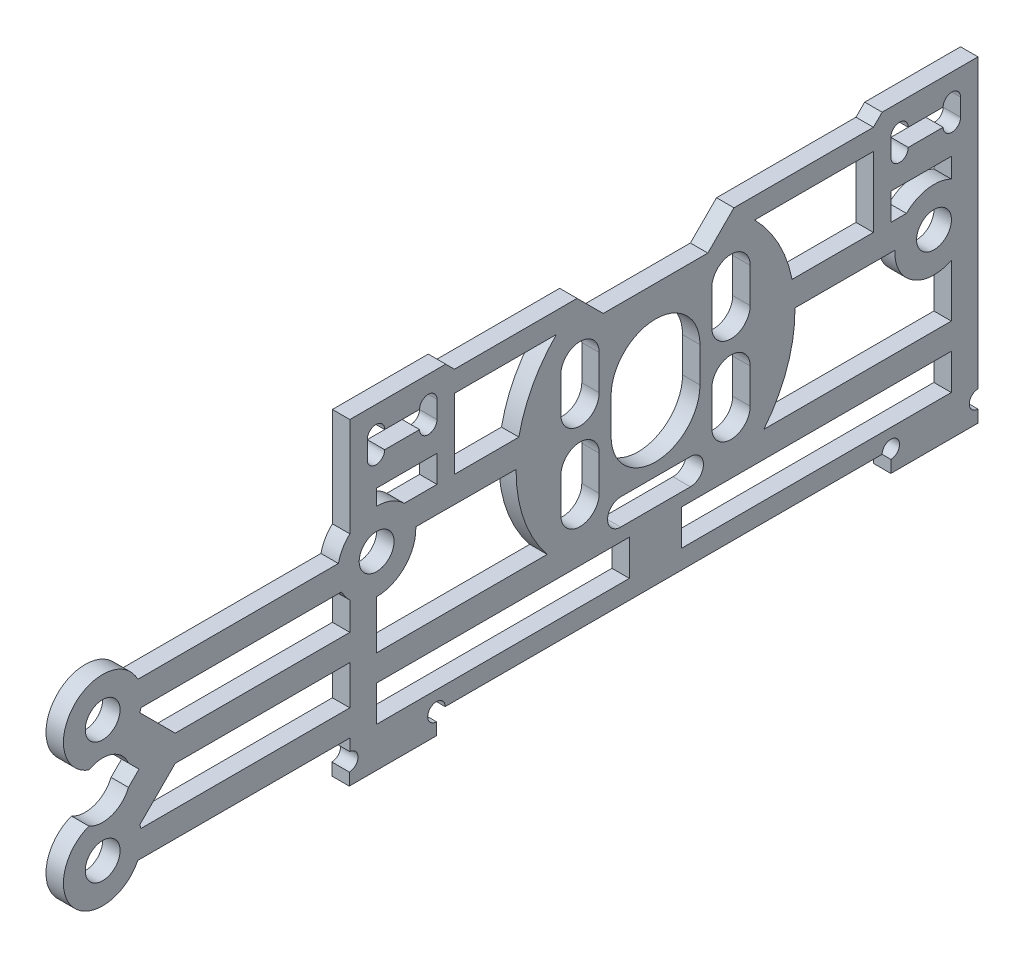
SolidWorks part; units mm, degrees
ref_plane "前视基准面" through (0, 0, 0) normal (0, 0, 1) x (1, 0, 0)
ref_plane "上视基准面" through (0, 0, 0) normal (0, 1, 0) x (1, 0, 0)
ref_plane "右视基准面" through (0, 0, 0) normal (1, 0, 0) x (0, 0, -1)
other "Configuration Table"
sketch "草图1" plane through (0, 0, 0) normal (1, 0, 0) x (0, 0, -1)
  line L11 (-27.6308, 1) -> (-27.6308, -1.7) construction
  line L41 (-27.6308, -1.7) -> (49.3482, -1.7) construction
  line L42 (21.9394, 13) -> (21.9394, 18) construction
  line L48 (21.9394, 11.675) -> (21.9394, 13.675) construction
  line L54 (26.2694, 16.1749) -> (26.2694, 14.1749) construction
  line L64 (19.3894, 11.675) -> (19.3894, 13.675)
  line L77 (24.4894, 11.675) -> (24.4894, 13.675)
  line L85 (17.6103, 9.1756) -> (17.6103, 11.1756) construction
  line L88 (27.3694, 16.1749) -> (27.3694, 14.1749)
  line L107 (25.1694, 16.1749) -> (25.1694, 14.1749)
  line L113 (16.5103, 9.1756) -> (16.5103, 11.1756)
  line L133 (18.7103, 9.1756) -> (18.7103, 11.1756)
  line L139 (26.2685, 9.1756) -> (26.2685, 11.1756) construction
  line L150 (27.3685, 9.1756) -> (27.3685, 11.1756)
  line L151 (25.1685, 9.1756) -> (25.1685, 11.1756)
  line L152 (17.6094, 16.1749) -> (17.6094, 14.1749) construction
  line L153 (16.5094, 16.1749) -> (16.5094, 14.1749)
  line L154 (18.7094, 16.1749) -> (18.7094, 14.1749)
  line L215 (40.5394, 11.675) -> (5.9394, 11.675) construction
  line L229 (35.4394, 1.8) -> (35.4394, 2.5)
  line L254 (40.4394, 2.5) -> (40.4394, 1.8)
  line L255 (9.8715, 3) -> (34.9394, 3)
  line L256 (4.3715, 2.5) -> (4.3715, 1.8)
  line L257 (4.8719, 3) -> (3.8711, 3) construction
  line L259 (-8.2953, 9.2793) -> (-7.691, 8.675)
  line L260 (9.3715, 1.8) -> (9.3715, 2.5)
  line L261 (9.8715, 3) -> (8.8715, 3) construction
  line L269 (10.403, 17.8) -> (10.403, 14.275)
  line L273 (4.403, 17.8) -> (4.403, 14.3188)
  line L282 (40.4394, 14.275) -> (40.4394, 3.5)
  line L284 (40.4394, 17.8) -> (40.4394, 14.275)
  line L287 (34.4394, 17.8) -> (34.4394, 14.275)
  line L302 (4.403, 4.175) -> (4.403, 3.499)
  line L304 (4.403, 17.8) -> (4.403, 18.3)
  line L305 (36.4394, 17.5) -> (38.4394, 17.5)
  line L307 (-7.7613, 13.175) -> (3.7457, 13.175)
  line L308 (4.3715, 1.8) -> (9.3715, 1.8)
  line L311 (34.4394, 17.8) -> (34.4394, 18.3)
  line L312 (4.403, 18.3) -> (4.403, 19.5)
  line L313 (40.4394, 18.3) -> (40.4394, 17.8)
  line L314 (6.403, 18.5) -> (8.403, 18.5)
  line L317 (10.403, 18.3) -> (10.403, 17.8)
  line L321 (40.4394, 19.5) -> (40.4394, 18.3)
  line L322 (10.403, 19.5) -> (17.4394, 19.5)
  line L326 (10.403, 14.275) -> (14.101, 14.275)
  line L330 (10.403, 18.3) -> (16.2508, 18.3)
  line L331 (34.4394, 14.275) -> (29.7778, 14.275)
  line L332 (27.628, 18.3) -> (34.4394, 18.3)
  line L333 (5.403, 18.5) -> (5.403, 17.5)
  line L334 (26.4394, 19.5) -> (34.4394, 19.5)
  line L353 (9.403, 18.5) -> (9.403, 17.5)
  line L354 (6.403, 17.5) -> (8.403, 17.5)
  line L355 (35.4394, 18.5) -> (35.4394, 17.5)
  line L356 (36.4394, 18.5) -> (38.4394, 18.5)
  line L357 (39.4394, 18.5) -> (39.4394, 17.5)
  line L358 (4.403, 19.5) -> (4.403, 20)
  line L359 (40.4394, 19.5) -> (40.4394, 20)
  line L360 (40.4394, 20) -> (34.9394, 20)
  line L361 (34.9394, 20) -> (34.4394, 19.5)
  line L362 (4.403, 20) -> (9.903, 20)
  line L363 (10.403, 19.5) -> (9.903, 20)
  line L364 (34.4394, 18.3) -> (34.4394, 19.5) construction
  line L365 (10.403, 18.3) -> (10.403, 19.5) construction
  line L366 (35.4394, 1.8) -> (40.4394, 1.8)
  line L367 (-8.2953, 8.0707) -> (-7.691, 8.675)
  line L369 (3.9238, 11.675) -> (2.9394, 11.675) construction
  line L371 (3.9238, 11.675) -> (-7.5831, 11.675)
  line L372 (-7.7613, 4.175) -> (4.403, 4.175)
  line L373 (-7.6445, 11.4569) -> (-5.6126, 9.425)
  line L374 (4.403, 5.675) -> (-7.5831, 5.675)
  line L375 (4.403, 7.925) -> (4.403, 5.675)
  line L376 (4.403, 9.425) -> (-5.6126, 9.425)
  line L378 (-5.6126, 7.925) -> (4.403, 7.925)
  line L379 (4.403, 11.0312) -> (4.403, 9.425)
  line L380 (-7.6445, 5.8931) -> (-5.6126, 7.925)
  line L381 (21.9394, 18) -> (18.9394, 18)
  line L382 (18.9394, 18) -> (17.4394, 19.5)
  line L383 (21.9394, 18) -> (24.9394, 18)
  line L384 (24.9394, 18) -> (26.4394, 19.5)
  arc A86 (19.3894, 11.675) -> (24.4894, 11.675) centre (21.9394, 11.675) ccw
  arc A87 (24.4894, 13.675) -> (19.3894, 13.675) centre (21.9394, 13.675) ccw
  arc A88 (27.3685, 9.1756) -> (25.1685, 9.1756) centre (26.2685, 9.1756) cw
  arc A89 (27.3694, 16.1749) -> (25.1694, 16.1749) centre (26.2694, 16.1749) ccw
  arc A90 (25.1694, 14.1749) -> (27.3694, 14.1749) centre (26.2694, 14.1749) ccw
  arc A91 (16.5103, 9.1756) -> (18.7103, 9.1756) centre (17.6103, 9.1756) ccw
  arc A92 (18.7103, 11.1756) -> (16.5103, 11.1756) centre (17.6103, 11.1756) ccw
  arc A93 (25.1685, 11.1756) -> (27.3685, 11.1756) centre (26.2685, 11.1756) cw
  arc A94 (16.5094, 16.1749) -> (18.7094, 16.1749) centre (17.6094, 16.1749) cw
  arc A95 (18.7094, 14.1749) -> (16.5094, 14.1749) centre (17.6094, 14.1749) cw
  circle A130 centre (5.9394, 12.675) radius 1
  circle A139 centre (-9.7768, 8.675) radius 5 construction
  circle A141 centre (-9.7768, 12.175) radius 1
  circle A142 centre (-9.7768, 5.175) radius 1
  circle A148 centre (37.9149, 12.675) radius 1
  arc A149 (4.3715, 2.5) -> (4.403, 3.499) centre (4.3715, 3) ccw
  arc A150 (9.8715, 3) -> (9.3715, 2.5) centre (9.3715, 3) ccw
  arc A151 (35.4394, 2.5) -> (34.9394, 3) centre (35.4394, 3) ccw
  arc A152 (40.4394, 3.5) -> (40.4394, 2.5) centre (40.4394, 3) ccw
  arc A180 (16.2508, 18.3) -> (14.101, 14.275) centre (21.9394, 12.675) ccw
  arc A181 (29.7778, 14.275) -> (27.628, 18.3) centre (21.9394, 12.675) ccw
  arc A184 (4.403, 14.3188) -> (3.7457, 13.175) centre (5.9394, 12.675) ccw
  arc A185 (6.403, 18.5) -> (5.403, 18.5) centre (5.903, 18.5) ccw
  arc A186 (5.403, 17.5) -> (6.403, 17.5) centre (5.903, 17.5) ccw
  arc A187 (9.403, 18.5) -> (8.403, 18.5) centre (8.903, 18.5) ccw
  arc A188 (8.403, 17.5) -> (9.403, 17.5) centre (8.903, 17.5) ccw
  arc A189 (39.4394, 18.5) -> (38.4394, 18.5) centre (38.9394, 18.5) ccw
  arc A190 (38.4394, 17.5) -> (39.4394, 17.5) centre (38.9394, 17.5) ccw
  arc A191 (36.4394, 18.5) -> (35.4394, 18.5) centre (35.9394, 18.5) ccw
  arc A192 (35.4394, 17.5) -> (36.4394, 17.5) centre (35.9394, 17.5) ccw
  arc A195 (-10.5648, 7.2825) -> (-8.2953, 8.0707) centre (-9.7768, 8.675) ccw
  arc A196 (-7.6445, 11.4569) -> (-7.5831, 11.675) centre (-9.7768, 12.175) ccw
  arc A197 (-10.5648, 7.2825) -> (-7.7613, 4.175) centre (-9.7768, 5.175) ccw
  arc A198 (-8.2953, 9.2793) -> (-10.5648, 10.0675) centre (-9.7768, 8.675) ccw
  arc A199 (3.9238, 11.675) -> (4.403, 11.0312) centre (5.9394, 12.675) ccw
  arc A200 (-7.7613, 13.175) -> (-10.5648, 10.0675) centre (-9.7768, 12.175) ccw
  arc A201 (-7.5831, 5.675) -> (-7.6445, 5.8931) centre (-9.7768, 5.175) ccw
  point P37 (21.9394, 17.275)
  point P62 (21.9394, 12.675)
  point P82 (26.2694, 15.1749)
  point P88 (26.2685, 10.1756)
  point P96 (17.6103, 10.1756)
  point P105 (17.6094, 15.1749)
  point P144 (21.9394, 19.5)
extrude "凸台-拉伸1" add sketch "草图1" along normal blind 1
sketch "草图2" plane through (1, 0, 0) normal (1, 0, 0) x (0, 0, -1)
  line L9 (9.403, 12.775) -> (8.1872, 12.775)
  line L10 (5.9394, 15.8232) -> (9.403, 15.8232)
  line L19 (5.9394, 4.089) -> (20.4394, 4.089)
  line L29 (5.9394, 5.6376) -> (5.9394, 6.1376)
  line L32 (5.9394, 10.425) -> (5.9394, 7.6376)
  line L33 (23.9394, 7.6376) -> (19.9394, 7.6376) construction
  line L34 (38.9078, 10.656) -> (38.9078, 7.6376)
  line L36 (38.9078, 5.6376) -> (38.9078, 6.1376)
  line L37 (9.403, 15.5523) -> (9.403, 15.8232)
  line L38 (20.4394, 5.6376) -> (20.4394, 5.8376)
  line L39 (35.4394, 15.8232) -> (38.9078, 15.8232)
  line L40 (9.403, 15.5523) -> (9.403, 14.275)
  line L41 (38.9078, 15.8232) -> (38.9078, 14.6941)
  line L42 (5.9394, 15.8232) -> (5.9394, 14.925)
  line L43 (34.4394, 12.775) -> (29.9388, 12.775)
  line L44 (23.4394, 4.089) -> (23.4394, 5.6376)
  line L45 (23.4394, 4.089) -> (38.9078, 4.089)
  line L46 (20.4394, 5.6376) -> (20.4394, 4.089)
  line L47 (9.403, 12.775) -> (13.9398, 12.7576)
  line L48 (34.4394, 12.775) -> (35.6671, 12.775)
  line L50 (7.5213, 14.275) -> (9.403, 14.275)
  line L51 (36.3329, 14.275) -> (35.4394, 14.275)
  line L52 (35.4394, 15.8232) -> (35.4394, 14.275)
  line L59 (5.9394, 5.6376) -> (5.9394, 4.089)
  line L60 (38.9078, 5.6376) -> (38.9078, 4.089)
  line L61 (19.4369, 6.1376) -> (20.4394, 6.1376)
  line L62 (23.4394, 5.8376) -> (23.4394, 5.6376)
  line L63 (20.4394, 6.1376) -> (20.4394, 5.8376)
  line L64 (15.7245, 7.6376) -> (5.9394, 7.6376)
  line L66 (5.9394, 6.1376) -> (19.4369, 6.1376)
  line L68 (38.9078, 7.6376) -> (28.1543, 7.6376)
  line L69 (24.4419, 6.1376) -> (38.9078, 6.1376)
  line L70 (24.4419, 6.1376) -> (23.4394, 6.1376)
  line L71 (23.4394, 6.1376) -> (23.4394, 5.8376)
  line L73 (23.9394, 6.8876) -> (19.9394, 6.8876)
  line L74 (23.9394, 8.3876) -> (19.9394, 8.3876)
  arc A19 (5.9394, 10.425) -> (8.1872, 12.775) centre (5.9394, 12.675) ccw
  arc A24 (13.9398, 12.7576) -> (15.7245, 7.6376) centre (21.9394, 12.675) ccw
  arc A25 (38.9078, 14.6941) -> (36.3329, 14.275) centre (37.9149, 12.675) ccw
  arc A26 (28.1543, 7.6376) -> (29.9388, 12.775) centre (21.9394, 12.675) ccw
  arc A27 (23.9394, 6.8876) -> (23.9394, 8.3876) centre (23.9394, 7.6376) ccw
  arc A28 (19.9394, 8.3876) -> (19.9394, 6.8876) centre (19.9394, 7.6376) ccw
  arc A29 (7.5213, 14.275) -> (5.9394, 14.925) centre (5.9394, 12.675) ccw
  arc A30 (35.6671, 12.775) -> (38.9078, 10.656) centre (37.9149, 12.675) ccw
  point P45 (21.9394, 7.6376)
extrude "切除-拉伸1" cut sketch "草图2" against normal blind 1
